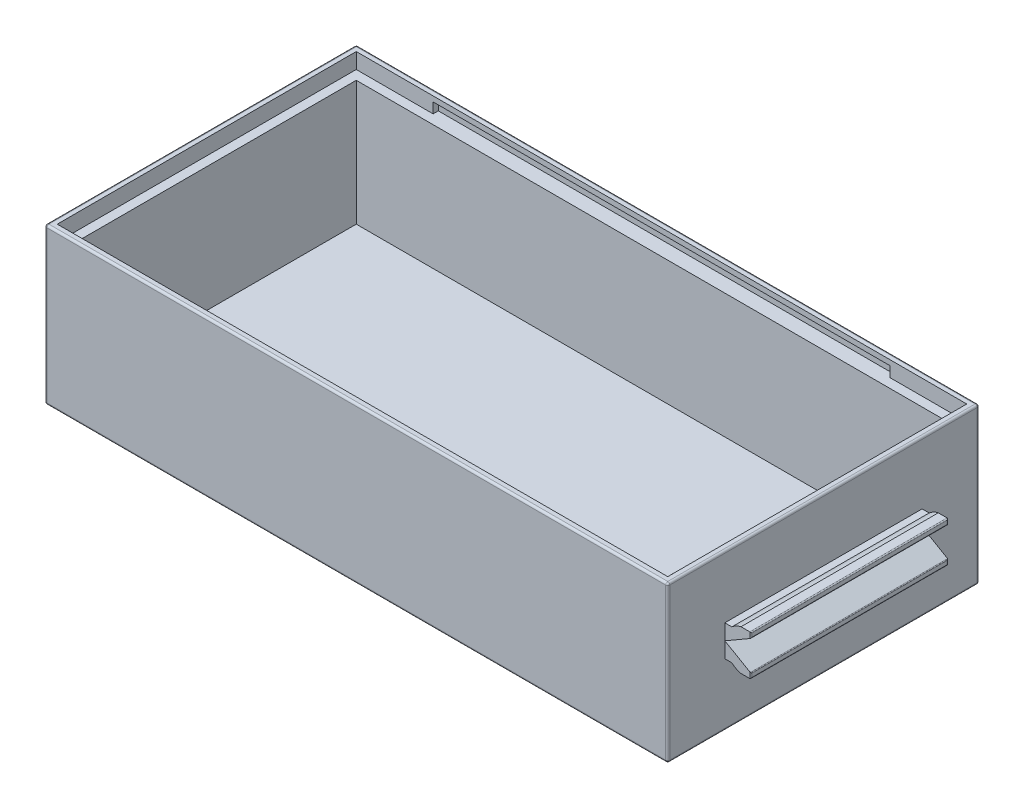
SolidWorks part; units mm, degrees
ref_plane "前视基准面" through (0, 0, 0) normal (0, 0, 1) x (1, 0, 0)
ref_plane "上视基准面" through (0, 0, 0) normal (0, 1, 0) x (1, 0, 0)
ref_plane "右视基准面" through (0, 0, 0) normal (1, 0, 0) x (0, 0, -1)
sketch "草图1" plane through (0, 0, 0) normal (0, 1, 0) x (1, 0, 0)
  line L0 (30, 15) -> (30, -15)
  line L1 (30, 15) -> (-30, 15)
  line L2 (30, -15) -> (-30, -15)
  line L3 (-30, 15) -> (-30, -15)
  line L4 (30, 15) -> (-30, -15) construction
  line L5 (30, -15) -> (-30, 15) construction
  point P1 (0, 0)
  dimension "D1" = 60
  dimension "D2" = 30
extrude "凸台-拉伸1" add sketch "草图1" along normal blind 15
sketch "草图2" plane through (0, 15, 0) normal (0, 1, 0) x (1, 0, 0)
  line L0 (29.4, 14.4) -> (29.4, -14.4)
  line L1 (29.4, 14.4) -> (-29.4, 14.4)
  line L2 (29.4, -14.4) -> (-29.4, -14.4)
  line L3 (-29.4, 14.4) -> (-29.4, -14.4)
  line L4 (29.4, 14.4) -> (-29.4, -14.4) construction
  line L5 (29.4, -14.4) -> (-29.4, 14.4) construction
  point P1 (0, 0)
  dimension "D1" = 58.8
  dimension "D2" = 28.8
extrude "切除-拉伸2" cut sketch "草图2" against normal blind 1.5
sketch "草图4" plane through (0, 13.5, 0) normal (0, 1, 0) x (1, 0, 0)
  line L0 (28.5, 13.5) -> (28.5, -13.5)
  line L1 (28.5, 13.5) -> (-28.5, 13.5)
  line L2 (28.5, -13.5) -> (-28.5, -13.5)
  line L3 (-28.5, 13.5) -> (-28.5, -13.5)
  line L4 (28.5, 13.5) -> (-28.5, -13.5) construction
  line L5 (28.5, -13.5) -> (-28.5, 13.5) construction
  point P1 (0, 0)
  dimension "D1" = 27
  dimension "D2" = 57
extrude "切除-拉伸3" cut sketch "草图4" against normal blind 12
sketch "草图5" plane through (0, 0, -14.4) normal (0, 0, 1) x (1, 0, 0)
  line L0 (28.5, 13.5) -> (-28.5, 13.5) construction
  line L1 (-22, 13.5) -> (22, 13.5)
  line L2 (-22, 13.5) -> (-22, 14.5)
  line L3 (-22, 14.5) -> (22, 14.5)
  line L4 (22, 13.5) -> (22, 14.5)
  line L5 (-30, 15) -> (-30, 0) construction
  line L6 (30, 15) -> (30, 0) construction
  dimension "D1" = 8
  dimension "D2" = 8
  dimension "D3" = 1
extrude "切除-拉伸4" cut sketch "草图5" against normal blind 0.5
mirror "镜向1" about plane through (0, 0, 0) normal (0, 0, 1) of "切除-拉伸4"
sketch "草图6" plane through (0, 0, 15) normal (0, 0, 1) x (1, 0, 0)
  line L0 (30, 7.5) -> (32, 7.5) construction
  line L1 (30, 15) -> (30, 0) construction
  line L2 (32, 7.5) -> (32.5, 7.5) construction
  line L3 (30, 7.5) -> (30, 9)
  line L4 (30, 9) -> (30.6771, 9)
  line L5 (32.5, 8.9434) -> (32.5, 9.45)
  line L6 (32.5, 9.45) -> (31.5556, 9.45)
  line L7 (30, 7.5) -> (32.5, 8.9434)
  line L8 (32.5, 8.9434) -> (32.5, 7.5) construction
  arc A0 (31.5556, 9.45) -> (30.6771, 9) centre (32, 7.5) ccw
  dimension "D5" = 2
  dimension "D1" = 2
  dimension "D2" = 0.5
  dimension "D3" = 1.5
  dimension "D4" = 1.95
  dimension "D6" = 30
extrude "凸台-拉伸4" add sketch "草图6" against normal blind 19 from offset 5.5 offset against normal yes
ref_plane "基准面1" through (0, 7.5, 0) normal (0, -1, 0) x (-1, 0, 0)
mirror "镜向2" about plane through (0, 7.5, 0) normal (0, -1, 0) of "凸台-拉伸4"
mirror "镜向3" about plane through (0, 0, 0) normal (1, 0, 0) of "凸台-拉伸4", "镜向2"
sketch "草图7" plane through (0, 0, 0) normal (0, 0, 1) x (1, 0, 0)
  line L0 (-30, 0) -> (-22.5, 0) construction
  line L1 (-30, 0) -> (30, 0) construction
  line L2 (-22.5, 0) -> (-22.5, -2) construction
  line L3 (-22.5, -2) -> (-22.5, -2.5) construction
  line L4 (-24, 0) -> (-21, 0)
  line L5 (-21, 0) -> (-21, -0.6771)
  line L6 (-24.45, -2.5) -> (-20.55, -2.5)
  line L7 (-20.55, -2.5) -> (-20.55, -1.5556)
  line L8 (-24.45, -2.5) -> (-24.45, -1.5556)
  line L9 (-24, 0) -> (-24, -0.6771)
  arc A0 (-20.55, -1.5556) -> (-21, -0.6771) centre (-22.5, -2) ccw
  arc A1 (-24.45, -1.5556) -> (-24, -0.6771) centre (-22.5, -2) cw
  dimension "D6" = 2
  dimension "D1" = 7.5
  dimension "D2" = 2
  dimension "D3" = 0.5
  dimension "D4" = 1.5
  dimension "D5" = 1.95
extrude "凸台-拉伸5" add sketch "草图7" along normal blind 2 and the other way blind 2
pattern_linear "阵列(线性)1" count 4 spacing 15 along (1, 0, 0) of "凸台-拉伸5"
sketch "草图8" plane through (-30, 0, 0) normal (-1, 0, 0) x (0, 0, 1)
  line L0 (0, 0) -> (0, -2) construction
  line L1 (0, -2) -> (0, -2.5) construction
  line L2 (-2, -2.5) -> (2, -2.5) construction
  line L3 (0, 0) -> (1.5, 0) construction
  line L4 (-15, 0) -> (15, 0) construction
  line L5 (1.5, 0) -> (1.5, -0.6771)
  line L6 (0, -2.5) -> (1.95, -2.5) construction
  line L7 (1.95, -2.5) -> (1.95, -1.5556)
  line L8 (1.95, -2.5) -> (2, -2.5)
  line L9 (2, -2.5) -> (2, 0)
  line L10 (2, 0) -> (1.5, 0)
  line L11 (-2, 0) -> (-1.5, 0)
  line L12 (-2, -2.5) -> (-2, 0)
  line L13 (-1.95, -2.5) -> (-2, -2.5)
  line L14 (-1.95, -2.5) -> (-1.95, -1.5556)
  line L15 (-1.5, 0) -> (-1.5, -0.6771)
  arc A0 (1.95, -1.5556) -> (1.5, -0.6771) centre (0, -2) ccw
  arc A1 (-1.95, -1.5556) -> (-1.5, -0.6771) centre (0, -2) cw
  dimension "D1" = 2
  dimension "D2" = 1.5
  dimension "D3" = 1.95
extrude "切除-拉伸5" cut sketch "草图8" against normal through all
fillet "圆角1" radius 0.2 12 edges at (30, 7.5, -15) (0, 15, -15) (-30, 7.5, -15) (0, 0, -15) (-30, 7.5, 15) (0, 15, 15) (30, 7.5, 15) (0, 0, 15) (-30, 0, 0) (30, 0, 0) (30, 15, 0) (-30, 15, 0)
fillet "圆角2" radius 0.1 32 edges at (24.45, -2.5, 0) (22.5, -2.5, -1.95) (20.55, -2.5, 0) (22.5, -2.5, 1.95) (9.45, -2.5, 0) (7.5, -2.5, -1.95) (5.55, -2.5, 0) (7.5, -2.5, 1.95) (-5.55, -2.5, 0) (-7.5, -2.5, -1.95) (-9.45, -2.5, 0) (-7.5, -2.5, 1.95) (-20.55, -2.5, 0) (-22.5, -2.5, -1.95) (-24.45, -2.5, 0) (-22.5, -2.5, 1.95) (-32.5, 8.9434, 0) (-32.5, 9.1967, -9.5) (-32.5, 9.45, 0) (-32.5, 9.1967, 9.5) (-32.5, 5.55, 0) (-32.5, 5.8033, -9.5) (-32.5, 6.0566, 0) (-32.5, 5.8033, 9.5) (32.5, 6.0566, 0) (32.5, 5.8033, -9.5) (32.5, 5.55, 0) (32.5, 5.8033, 9.5) (32.5, 9.45, 0) (32.5, 9.1967, -9.5) (32.5, 8.9434, 0) (32.5, 9.1967, 9.5)
